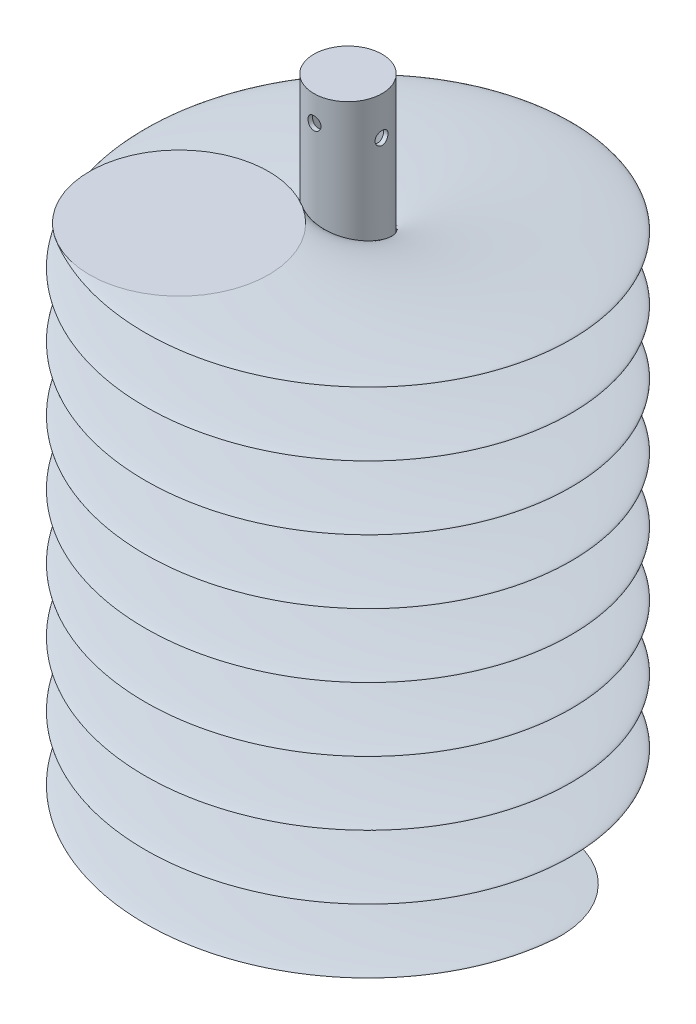
SolidWorks part; units mm, degrees
ref_plane "前视基准面" through (0, 0, 0) normal (0, 0, 1) x (1, 0, 0)
ref_plane "上视基准面" through (0, 0, 0) normal (0, 1, 0) x (1, 0, 0)
ref_plane "右视基准面" through (0, 0, 0) normal (1, 0, 0) x (0, 0, -1)
other "Configuration Table"
sketch "草图1" plane through (0, 0, 0) normal (0, 1, 0) x (1, 0, 0)
  circle A0 centre (0, 0) radius 16
  dimension "D1" = 32
extrude "凸台-拉伸1" add sketch "草图1" along normal blind 300 contours A0
sketch "草图5" plane through (0, 0, 0) normal (0, 1, 0) x (1, 0, 0)
  circle A0 centre (0, 0) radius 16
  dimension "D1" = 32
curve "螺旋线/涡状线1" pitch 30 height 250 turns 8.3333
sketch "草图9" plane through (0, 0, 0) normal (0, 1, 0) x (1, 0, 0)
  circle A0 centre (58, 0) radius 42
  dimension "D1" = 58
sweep "扫描2" add profiles "草图9" path "螺旋线/涡状线1"
sketch "草图11" plane through (0, 0, 0) normal (0, 0, 1) x (1, 0, 0)
  line L0 (0, 0) -> (0, 276.1304) construction
ref_plane "基准面1" through (0, 2, 0) normal (0, 1, 0) x (1, 0, 0)
sketch "草图12" plane through (0, 2, 0) normal (0, 1, 0) x (1, 0, 0)
  circle A0 centre (0, 0) radius 14
extrude "切除-拉伸1" cut sketch "草图12" along normal blind 296
sketch "草图14" plane through (0, 0, 0) normal (0, 0, 1) x (1, 0, 0)
  line L0 (0, -200000) -> (0, 200276.1304) construction
  line L1 (16, 300) -> (-16, 300) construction
  circle A0 centre (0, 288) radius 3.05
  dimension "D1" = 12
extrude "切除-拉伸2" cut sketch "草图14" against normal through all both and the other way through all
ref_plane "基准面2" through (0, 0, 0) normal (1, 0, 0) x (0, 1, 0)
sketch "草图15" plane through (0, 0, 0) normal (1, 0, 0) x (0, 1, 0)
  line L0 (-200000, 0) -> (200276.1304, 0) construction
  line L1 (300, -16) -> (300, 16) construction
  circle A0 centre (282, 0) radius 3.05
  dimension "D1" = 18
extrude "切除-拉伸3" cut sketch "草图15" against normal through all both and the other way through all
